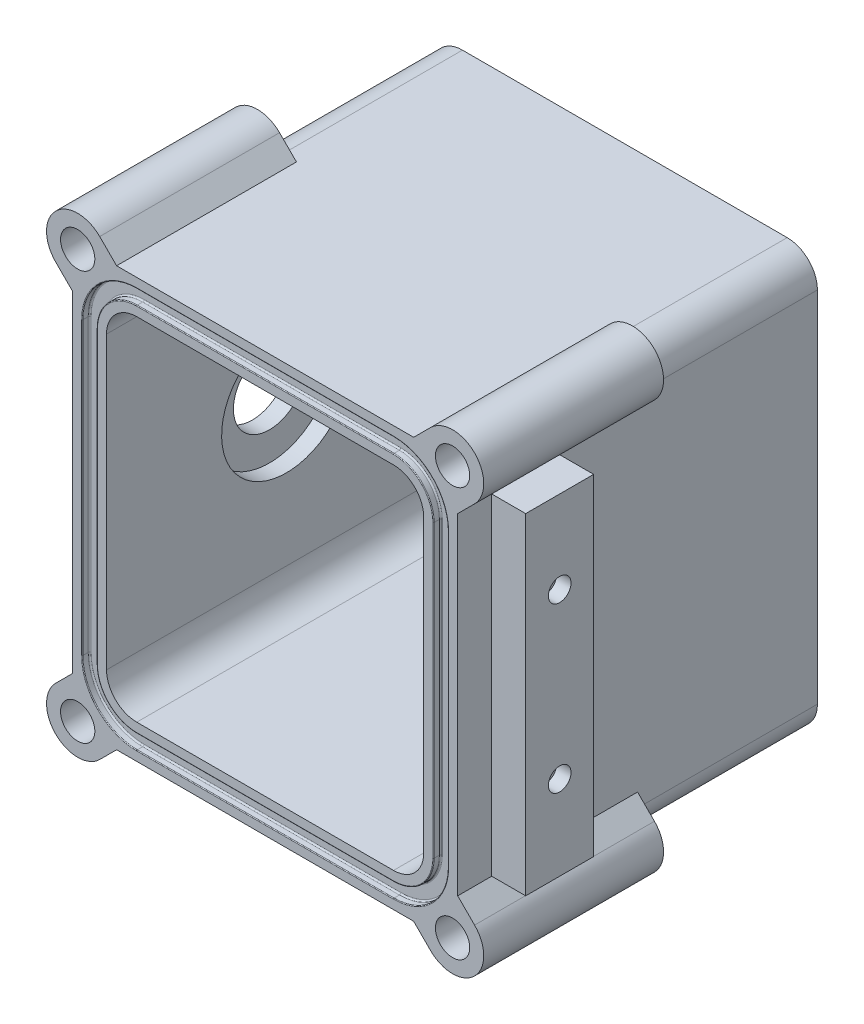
SolidWorks part; units mm, degrees
material "ABS"
ref_plane "X-Y Datum" through (0, 0, 0) normal (0, 0, 1) x (1, 0, 0)
ref_plane "X-Z Datum" through (0, 0, 0) normal (0, 1, 0) x (1, 0, 0)
ref_plane "Y-Z Datum" through (0, 0, 0) normal (1, 0, 0) x (0, 0, -1)
sketch "Sketch1" plane through (0, 0, 0) normal (0, 0, 1) x (1, 0, 0)
  line L0 (-34, -37) -> (-34, -16.68)
  line L1 (34, 37) -> (-34, 37)
  line L2 (34, 37) -> (34, -37)
  line L3 (34, -37) -> (-34, -37)
  line L5 (34, 37) -> (-34, -37) construction
  line L6 (34, -37) -> (-34, 37) construction
  line L7 (55.1739, 0) -> (-55.1739, 0) construction
  line L8 (-34, 37) -> (-34, 16.68)
  line L9 (-34, 16.68) -> (-34, -16.68)
  arc A0 (-34, -16.68) -> (-34, 16.68) centre (-14.8444, 0) cw construction
  point P0 (0, 0)
  dimension "D2" = 25.4
  dimension "D1" = 74
  dimension "D3" = 20.32
  dimension "D4" = 68
extrude "Boss-Extrude1" add sketch "Sketch1" along normal mid plane 63.5
shell "Shell1" thickness 6
fillet "Fillet1" radius 5.334 8 edges at (34, 37, 0) (34, -37, 0) (-34, -37, 0) (-34, 37, 0) (28, 31, 3) (28, -31, 3) (-28, -31, 3) (-28, 31, 3)
sketch "Sketch2" plane through (0, 0, 31.75) normal (0, 0, 1) x (1, 0, 0)
  line L21 (32.2827, -25.666) -> (32.2827, 25.666)
  line L22 (22.666, 35.2827) -> (-22.666, 35.2827)
  line L23 (-32.2827, 25.666) -> (-32.2827, -25.666)
  line L24 (-22.666, -35.2827) -> (22.666, -35.2827)
  line L25 (31, -25.666) -> (31, 25.666)
  line L26 (-22.666, -34) -> (22.666, -34)
  line L27 (-31, 25.666) -> (-31, -25.666)
  line L28 (22.666, 34) -> (-22.666, 34)
  line L29 (31, -25.666) -> (31, 25.666) construction
  line L30 (-22.666, -34) -> (22.666, -34) construction
  line L31 (-31, 25.666) -> (-31, -25.666) construction
  line L32 (22.666, 34) -> (-22.666, 34) construction
  line L33 (-29.7173, 25.666) -> (-29.7173, -25.666)
  line L34 (-22.666, -32.7173) -> (22.666, -32.7173)
  line L35 (29.7173, -25.666) -> (29.7173, 25.666)
  line L36 (22.666, 32.7173) -> (-22.666, 32.7173)
  arc A15 (32.2827, 25.666) -> (22.666, 35.2827) centre (22.666, 25.666) ccw
  arc A16 (-22.666, 35.2827) -> (-32.2827, 25.666) centre (-22.666, 25.666) ccw
  arc A17 (-32.2827, -25.666) -> (-22.666, -35.2827) centre (-22.666, -25.666) ccw
  arc A18 (22.666, -35.2827) -> (32.2827, -25.666) centre (22.666, -25.666) ccw
  arc A19 (31, 25.666) -> (22.666, 34) centre (22.666, 25.666) ccw
  arc A20 (22.666, -34) -> (31, -25.666) centre (22.666, -25.666) ccw
  arc A21 (-31, -25.666) -> (-22.666, -34) centre (-22.666, -25.666) ccw
  arc A22 (-22.666, 34) -> (-31, 25.666) centre (-22.666, 25.666) ccw
  arc A23 (31, 25.666) -> (22.666, 34) centre (22.666, 25.666) ccw construction
  arc A24 (22.666, -34) -> (31, -25.666) centre (22.666, -25.666) ccw construction
  arc A25 (-31, -25.666) -> (-22.666, -34) centre (-22.666, -25.666) ccw construction
  arc A26 (-22.666, 34) -> (-31, 25.666) centre (-22.666, 25.666) ccw construction
  arc A27 (-22.666, 32.7173) -> (-29.7173, 25.666) centre (-22.666, 25.666) ccw
  arc A28 (-29.7173, -25.666) -> (-22.666, -32.7173) centre (-22.666, -25.666) ccw
  arc A29 (22.666, -32.7173) -> (29.7173, -25.666) centre (22.666, -25.666) ccw
  arc A30 (29.7173, 25.666) -> (22.666, 32.7173) centre (22.666, 25.666) ccw
  dimension "D4" = 7.0513
  dimension "D5" = 2.5654
  dimension "D1" = 3
  dimension "D2" = 1.2827
  dimension "D3" = 1.2827
extrude "Cut-Extrude1" cut sketch "Sketch2" against normal blind 1.2954
fillet "Fillet2" radius 0.254 16 edges at (27.652, -30.652, 30.4546) (0, -32.7173, 30.4546) (-27.652, -30.652, 30.4546) (-29.7173, 0, 30.4546) (-27.652, 30.652, 30.4546) (0, 32.7173, 30.4546) (27.652, 30.652, 30.4546) (-29.466, 32.466, 30.4546) (0, 35.2827, 30.4546) (29.466, 32.466, 30.4546) (32.2827, 0, 30.4546) (29.466, -32.466, 30.4546) (0, -35.2827, 30.4546) (-29.466, -32.466, 30.4546) (29.7173, 0, 30.4546) (-32.2827, 0, 30.4546)
fillet "Fillet3" radius 0.127 16 edges at (-29.466, -32.466, 31.75) (-32.2827, 0, 31.75) (-29.466, 32.466, 31.75) (0, 35.2827, 31.75) (29.466, 32.466, 31.75) (32.2827, 0, 31.75) (29.466, -32.466, 31.75) (-27.652, -30.652, 31.75) (-29.7173, 0, 31.75) (-27.652, 30.652, 31.75) (0, 32.7173, 31.75) (27.652, 30.652, 31.75) (29.7173, 0, 31.75) (27.652, -30.652, 31.75) (0, -35.2827, 31.75) (0, -32.7173, 31.75)
sketch "Sketch3" plane through (0, 0, 31.75) normal (0, 0, 1) x (1, 0, 0)
  line L0 (22.666, -25.666) -> (37.7124, -40.7124) construction
  line L1 (29.2023, -39.9805) -> (26.2218, -37)
  line L2 (-28.666, -37) -> (28.666, -37) construction
  line L3 (22.666, -25.666) -> (0, 0)
  line L5 (34, -29.2218) -> (36.9805, -32.2023)
  line L6 (34, -31.666) -> (34, 31.666) construction
  arc A0 (22.666, -35.4097) -> (32.4097, -25.666) centre (22.666, -25.666) ccw construction
  arc A1 (22.666, -35.4097) -> (32.4097, -25.666) centre (22.666, -25.666) ccw
  circle A2 centre (33.0914, -36.0914) radius 3.025
  circle A3 centre (33.0914, -36.0914) radius 5.5
  point P7 (29.5558, -32.5558)
  dimension "D1" = 6.05
  dimension "D3" = 11
  dimension "D2" = 5
extrude "Boss-Extrude2" add sketch "Sketch3" against normal blind 31.75
sketch "Sketch4" plane through (0, 0, 31.75) normal (0, 0, 1) x (1, 0, 0)
  circle A0 centre (33.0914, -36.0914) radius 3.025 construction
  circle A1 centre (33.0914, -36.0914) radius 3.025
  dimension "D1" = 6.05
extrude "Cut-Extrude2" cut sketch "Sketch4" against normal blind 9
mirror "Mirror1" about plane through (0, 0, 0) normal (0, 1, 0) of "Cut-Extrude2", "Boss-Extrude2"
mirror "Mirror2" about plane through (0, 0, 0) normal (1, 0, 0) of "Mirror1", "Cut-Extrude2", "Boss-Extrude2"
sketch "Sketch8" plane through (-34, 0, 0) normal (-1, 0, 0) x (0, 0, 1)
  line L0 (19.75, 29.2218) -> (19.75, -29.2218) construction
  line L11 (25.75, 29.2218) -> (25.75, -29.2218)
  line L12 (0, 29.2218) -> (31.75, 29.2218) construction
  line L13 (0, -29.2218) -> (31.75, -29.2218) construction
  line L14 (25.75, 29.2218) -> (13.75, 29.2218)
  line L15 (13.75, 29.2218) -> (13.75, -29.2218)
  line L16 (13.75, -29.2218) -> (25.75, -29.2218)
  line L17 (13.75, 0) -> (25.75, 0) construction
  line L18 (25.75, 29.2218) -> (13.75, 29.2218)
  line L19 (25.75, -29.2218) -> (13.75, -29.2218)
  point P0 (0, 0)
  line M1 (31.75, 29.2218) -> (0, 29.2218)
  line M7 (0, -29.2218) -> (31.75, -29.2218)
extrude "Boss-Extrude3" add sketch "Sketch8" along normal blind 6 contours L15 L11 M1 M7
sketch "Sketch12" plane through (-40, 0, 0) normal (-1, 0, 0) x (0, 0, 1)
  line L0 (19.75, 29.2218) -> (19.75, -29.2218) construction
  line L1 (25.75, 29.2218) -> (13.75, 29.2218) construction
  line L2 (13.75, -29.2218) -> (25.75, -29.2218) construction
  line L3 (13.75, 0) -> (25.75, 0) construction
  line L4 (13.75, 29.2218) -> (13.75, -29.2218) construction
  line L5 (25.75, 29.2218) -> (25.75, -29.2218) construction
  circle A0 centre (19.75, 14.6168) radius 2
  circle A1 centre (19.75, -14.3392) radius 2
  dimension "D1" = 14.605
  dimension "D3" = 4
  dimension "D2" = 28.956
extrude "Cut-Extrude6" cut sketch "Sketch12" against normal blind 2.54
sketch "Sketch13" plane through (-34, 0, 0) normal (-1, 0, 0) x (0, 0, 1)
  line L0 (-31.75, 0) -> (31.75, 0) construction
  line L3 (-31.75, 31.666) -> (-31.75, -31.666) construction
  line L4 (31.75, 29.2218) -> (31.75, -29.2218) construction
  circle A0 centre (0, 0) radius 6.35
  dimension "D2" = 12.7
extrude "Cut-Extrude10" cut sketch "Sketch13" against normal blind 6
sketch "Sketch16" plane through (-28, 0, 0) normal (1, 0, 0) x (0, 0, -1)
  circle A0 centre (0, 0) radius 11.43
  dimension "D1" = 22.86
extrude "Cut-Extrude14" cut sketch "Sketch16" against normal blind 3
mirror "Mirror5" about plane through (0, 0, 0) normal (1, 0, 0) of "Boss-Extrude3"
mirror "Mirror6" about plane through (0, 0, 0) normal (1, 0, 0) of "Cut-Extrude6"
